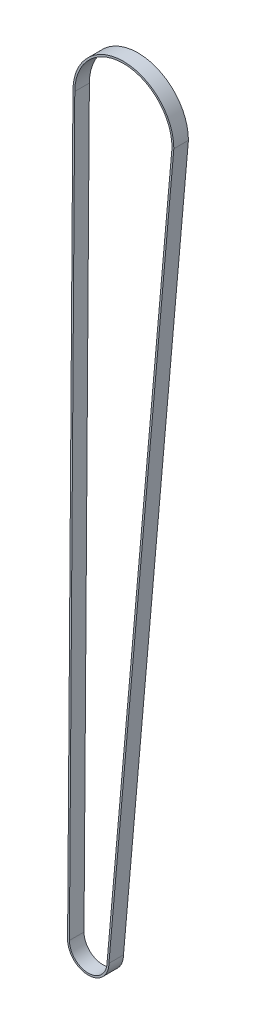
SolidWorks part; units mm, degrees
ref_plane "Front Plane" through (0, 0, 0) normal (0, 0, 1) x (1, 0, 0)
ref_plane "Top Plane" through (0, 0, 0) normal (0, 1, 0) x (1, 0, 0)
ref_plane "Right Plane" through (0, 0, 0) normal (1, 0, 0) x (0, 0, -1)
sketch "Sketch2" plane through (0, 0, 0) normal (0, 0, 1) x (1, 0, 0)
  line L0 (-9.2433, 157.6007) -> (-11.4531, -146.0051)
  line L1 (4.0469, -146.0051) -> (30.7567, 157.6007)
  line L2 (-9.9933, 157.6035) -> (-12.2031, -146.0024)
  line L3 (4.7968, -146.0388) -> (31.5066, 157.5675)
  arc A0 (-9.2433, 157.6007) -> (30.7567, 157.6007) centre (10.7567, 157.6007) cw
  arc A1 (-11.4531, -146.0051) -> (4.0469, -146.0051) centre (-3.7031, -146.0051) ccw
  arc A2 (-12.2031, -146.0024) -> (4.7968, -146.0388) centre (-3.7031, -146.0051) ccw
  arc A3 (-9.9933, 157.6035) -> (31.5066, 157.5675) centre (10.7567, 157.6007) cw
  dimension "D1" = 0.75
extrude "Boss-Extrude1" add sketch "Sketch2" along normal blind 6
